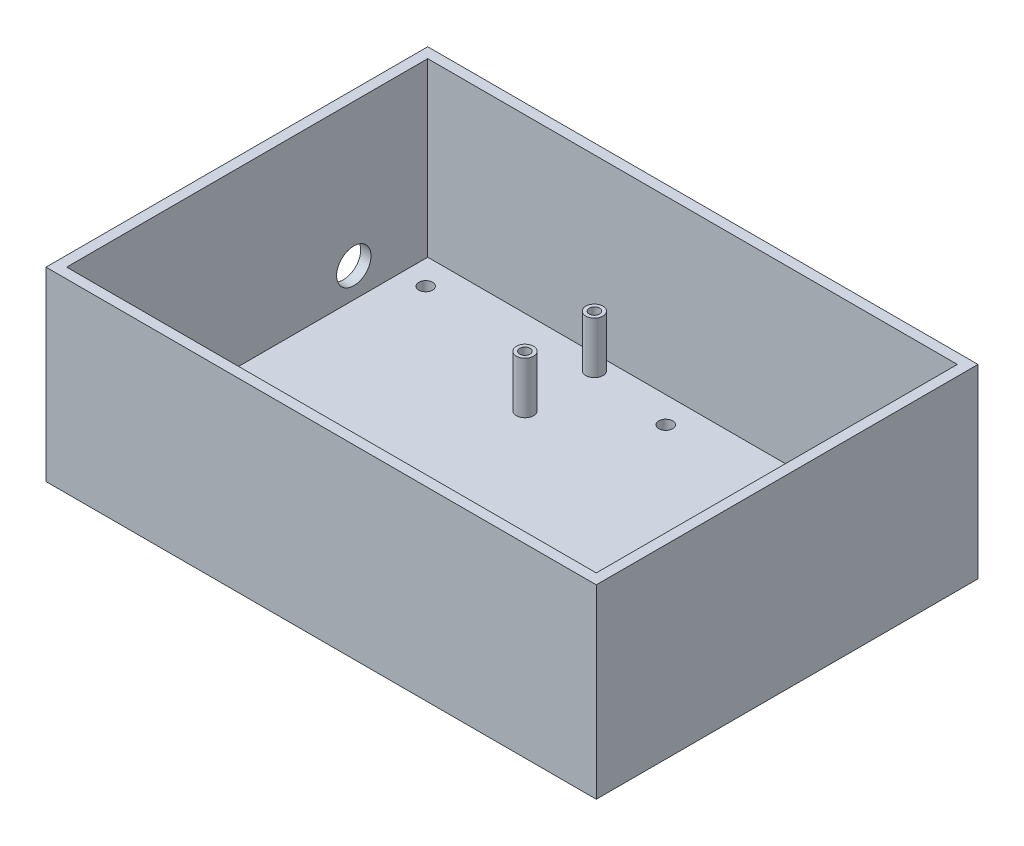
SolidWorks part; units mm, degrees
ref_plane "前视基准面" through (0, 0, 0) normal (0, 0, 1) x (1, 0, 0)
ref_plane "上视基准面" through (0, 0, 0) normal (0, 1, 0) x (1, 0, 0)
ref_plane "右视基准面" through (0, 0, 0) normal (1, 0, 0) x (0, 0, -1)
sketch "草图1" plane through (0, 0, 0) normal (0, 1, 0) x (1, 0, 0)
  line L0 (-95.7563, 0) -> (119.1586, 0) construction
  line L1 (-81.9246, 55.5) -> (78.0754, 55.5)
  line L2 (-81.9246, 55.5) -> (-81.9246, -55.5)
  line L3 (-81.9246, -55.5) -> (78.0754, -55.5)
  line L4 (78.0754, 55.5) -> (78.0754, -55.5)
  line L5 (-75.7892, 49.66) -> (9.2321, 49.66) construction
  circle A0 centre (-71.9246, 44.9) radius 2
  circle A1 centre (-71.9246, -44.9) radius 2
  circle A2 centre (-2.1246, 44.9) radius 2
  circle A3 centre (-2.1246, -44.9) radius 2
  circle A4 centre (-26.1246, 48.16) radius 1.5
  circle A5 centre (-26.1246, 27.96) radius 1.5
  point P0 (0, 0)
  dimension "D3" = 89.8
  dimension "D5" = 69.8
  dimension "D7" = 20.2
  dimension "D8" = 24
  dimension "D1" = 111
  dimension "D2" = 160
  dimension "D4" = 10
  dimension "D6" = 4.76
extrude "凸台-拉伸1" add sketch "草图1" along normal blind 4
sketch "草图2" plane through (0, 4, 0) normal (0, 1, 0) x (1, 0, 0)
  line L4 (78.0754, 55.5) -> (-81.9246, 55.5)
  line L5 (-81.9246, 55.5) -> (-81.9246, -55.5)
  line L6 (-81.9246, -55.5) -> (78.0754, -55.5)
  line L7 (78.0754, -55.5) -> (78.0754, 55.5)
  line L8 (75.0754, -52.5) -> (75.0754, 52.5)
  line L9 (-78.9246, -52.5) -> (75.0754, -52.5)
  line L10 (-78.9246, 52.5) -> (-78.9246, -52.5)
  line L11 (75.0754, 52.5) -> (-78.9246, 52.5)
  line L12 (75.0754, -52.5) -> (75.0754, 52.5)
  line L13 (-78.9246, -52.5) -> (75.0754, -52.5)
  line L14 (-78.9246, 52.5) -> (-78.9246, -52.5)
  line L15 (75.0754, 52.5) -> (-78.9246, 52.5)
  dimension "D1" = 3
  dimension "D2" = 3
sketch "草图3" plane through (0, 4, 0) normal (0, 1, 0) x (1, 0, 0)
  circle A0 centre (-26.1246, 48.16) radius 2.5
  circle A1 centre (-26.1246, 48.16) radius 1.5
  circle A2 centre (-26.1246, 27.96) radius 1.5
  circle A3 centre (-26.1246, 27.96) radius 2.5
  dimension "D1" = 3
  dimension "D2" = 5
  dimension "D3" = 5
extrude "凸台-拉伸4" add sketch "草图2" along normal blind 50 separate body
extrude "凸台-拉伸5" add sketch "草图3" along normal blind 15
sketch "草图4" plane through (-81.9246, 0, 0) normal (-1, 0, 0) x (0, 0, 1)
  line L0 (-55.5, 54) -> (-55.5, 0) construction
  line L1 (-55.5, 0) -> (55.5, 0) construction
  circle A0 centre (-31, 12.58) radius 5
  dimension "D1" = 24.5
  dimension "D2" = 12.58
  dimension "D3" = 10
extrude "切除-拉伸1" cut sketch "草图4" against normal blind 5
